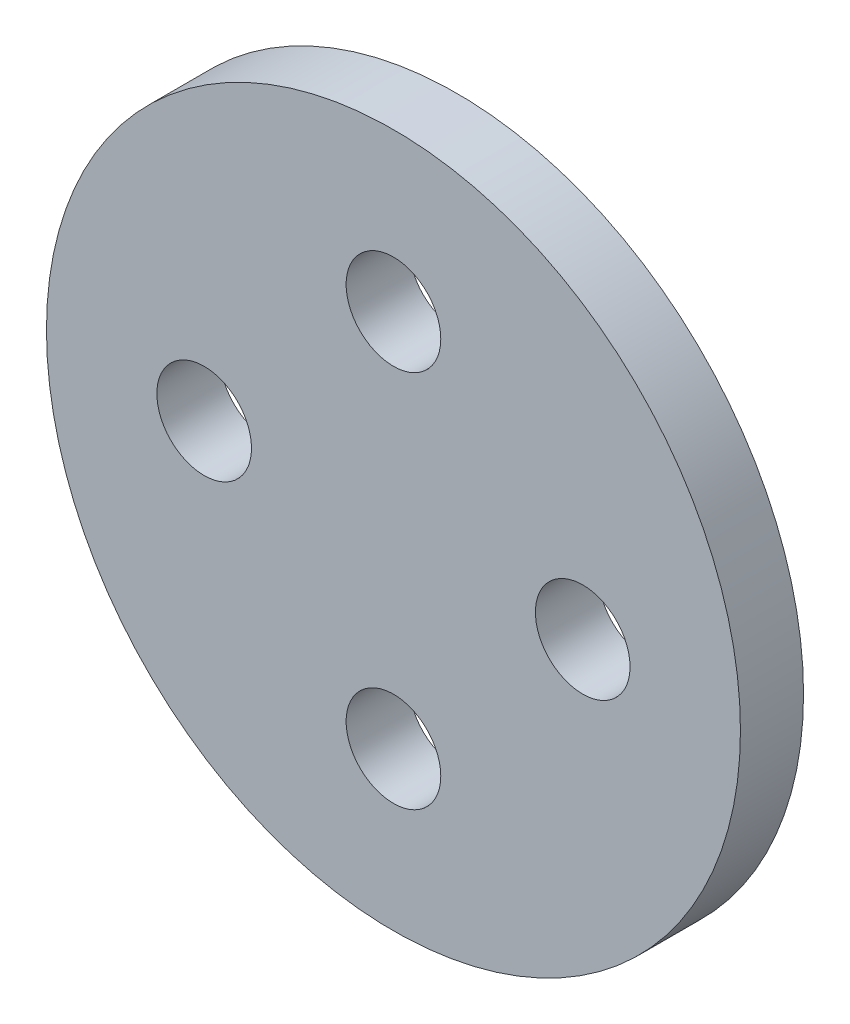
SolidWorks part; units mm, degrees
ref_plane "Front Plane" through (0, 0, 0) normal (0, 0, 1) x (1, 0, 0)
ref_plane "Top Plane" through (0, 0, 0) normal (0, 1, 0) x (1, 0, 0)
ref_plane "Right Plane" through (0, 0, 0) normal (1, 0, 0) x (0, 0, -1)
sketch "Sketch1" plane through (0, 0, 0) normal (0, 0, 1) x (1, 0, 0)
  circle A0 centre (0, 0) radius 17.4625
  circle A1 centre (0, 9.525) radius 2.3812
  circle A2 centre (9.525, 0) radius 2.3813
  circle A3 centre (0, -9.525) radius 2.3813
  circle A4 centre (-9.525, 0) radius 2.3813
  point P14 (0, 0)
  dimension "D1" = 34.925
  dimension "D2" = 4.7625
  dimension "D3" = 9.525
  dimension "D4" = 4
extrude "Boss-Extrude1" add sketch "Sketch1" along normal blind 3.175
